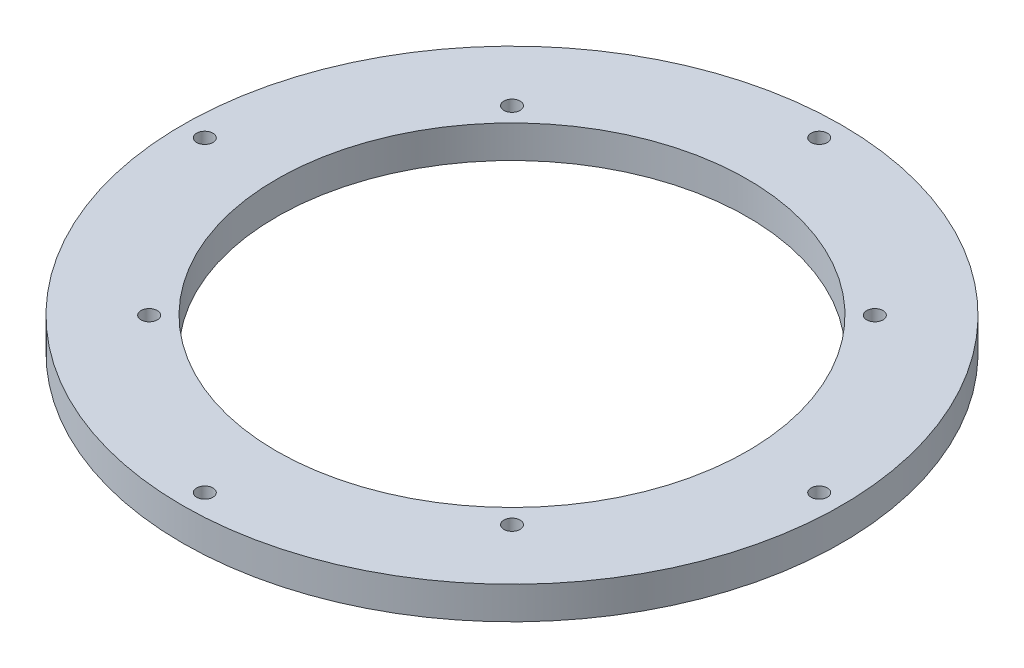
SolidWorks part; units mm, degrees
material "合金钢 (SS)"
ref_plane "前视基准面" through (0, 0, 0) normal (0, 0, 1) x (1, 0, 0)
ref_plane "上视基准面" through (0, 0, 0) normal (0, 1, 0) x (1, 0, 0)
ref_plane "右视基准面" through (0, 0, 0) normal (1, 0, 0) x (0, 0, -1)
other "Configuration Table"
sketch "草图2" plane through (0, 0, 0) normal (0, 1, 0) x (1, 0, 0)
  circle A0 centre (0, 0) radius 101.25
  circle A1 centre (0, 0) radius 72.35
  dimension "D1" = 202.5
  dimension "D2" = 144.7
extrude "凸台-拉伸1" add sketch "草图2" along normal blind 10
sketch "草图3" plane through (0, 10, 0) normal (0, 1, 0) x (1, 0, 0)
  line L0 (0, 0) -> (94.385, 0) construction
  line L1 (0, 0) -> (66.7403, 66.7403) construction
  circle A0 centre (0, 0) radius 94.385 construction
  circle A1 centre (0, 0) radius 78.83 construction
  circle A2 centre (0, 94.385) radius 2.5
  circle A3 centre (55.7412, 55.7412) radius 2.5
  circle A4 centre (94.385, 0) radius 2.5
  circle A5 centre (0, -94.385) radius 2.5
  circle A6 centre (-94.385, 0) radius 2.5
  circle A7 centre (55.7412, -55.7412) radius 2.5
  circle A8 centre (-55.7412, -55.7412) radius 2.5
  circle A9 centre (-55.7412, 55.7412) radius 2.5
  dimension "D1" = 188.77
  dimension "D2" = 157.66
  dimension "D4" = 5
  dimension "D3" = 45
  dimension "D5" = 4
  dimension "D6" = 4
extrude "切除-拉伸1" cut sketch "草图3" against normal through all
